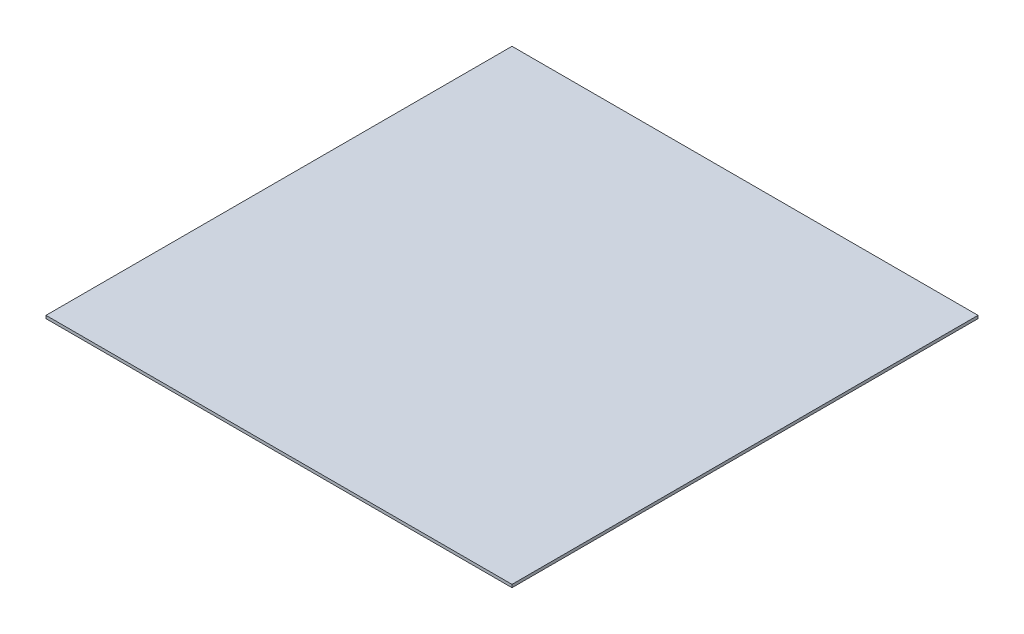
SolidWorks part; units mm, degrees
ref_plane "Front Plane" through (0, 0, 0) normal (0, 0, 1) x (1, 0, 0)
ref_plane "Top Plane" through (0, 0, 0) normal (0, 1, 0) x (1, 0, 0)
ref_plane "Right Plane" through (0, 0, 0) normal (1, 0, 0) x (0, 0, -1)
sketch "Sketch1" plane through (0, 0, 0) normal (0, 1, 0) x (1, 0, 0)
  line L1 (-40, 40) -> (40, 40)
  line L2 (-40, 40) -> (-40, -40)
  line L3 (-40, -40) -> (40, -40)
  line L4 (40, 40) -> (40, -40)
  line L5 (-40, 40) -> (40, -40) construction
  line L6 (-40, -40) -> (40, 40) construction
  point P0 (0, 0)
  dimension "D1" = 80
extrude "Boss-Extrude1" add sketch "Sketch1" along normal mid plane 0.5
